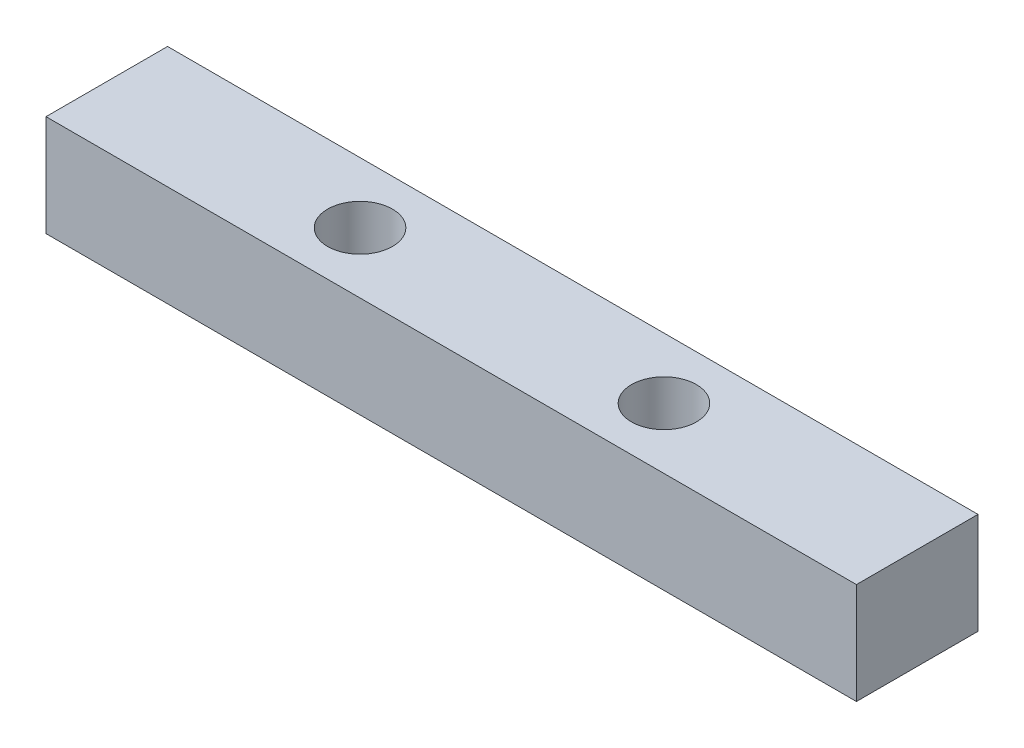
SolidWorks part; units mm, degrees
ref_plane "前视基准面" through (0, 0, 0) normal (0, 0, 1) x (1, 0, 0)
ref_plane "上视基准面" through (0, 0, 0) normal (0, 1, 0) x (1, 0, 0)
ref_plane "右视基准面" through (0, 0, 0) normal (1, 0, 0) x (0, 0, -1)
sketch "草图1" plane through (0, 0, 0) normal (0, 1, 0) x (1, 0, 0)
  line L0 (0, -55) -> (0, 55) construction
  line L2 (-20, -3) -> (20, -3)
  line L3 (-20, -3) -> (-20, 3)
  line L4 (-20, 3) -> (20, 3)
  line L5 (20, -3) -> (20, 3)
  line L6 (-20, -3) -> (20, 3) construction
  line L7 (-20, 3) -> (20, -3) construction
  circle A0 centre (-7.5, 0) radius 1.6
  circle A1 centre (7.5, 0) radius 1.6
  point P6 (0, 0)
  dimension "D1" = 3.2
  dimension "D2" = 15
  dimension "D3" = 40
  dimension "D4" = 6
extrude "凸台-拉伸1" add sketch "草图1" along normal blind 5
